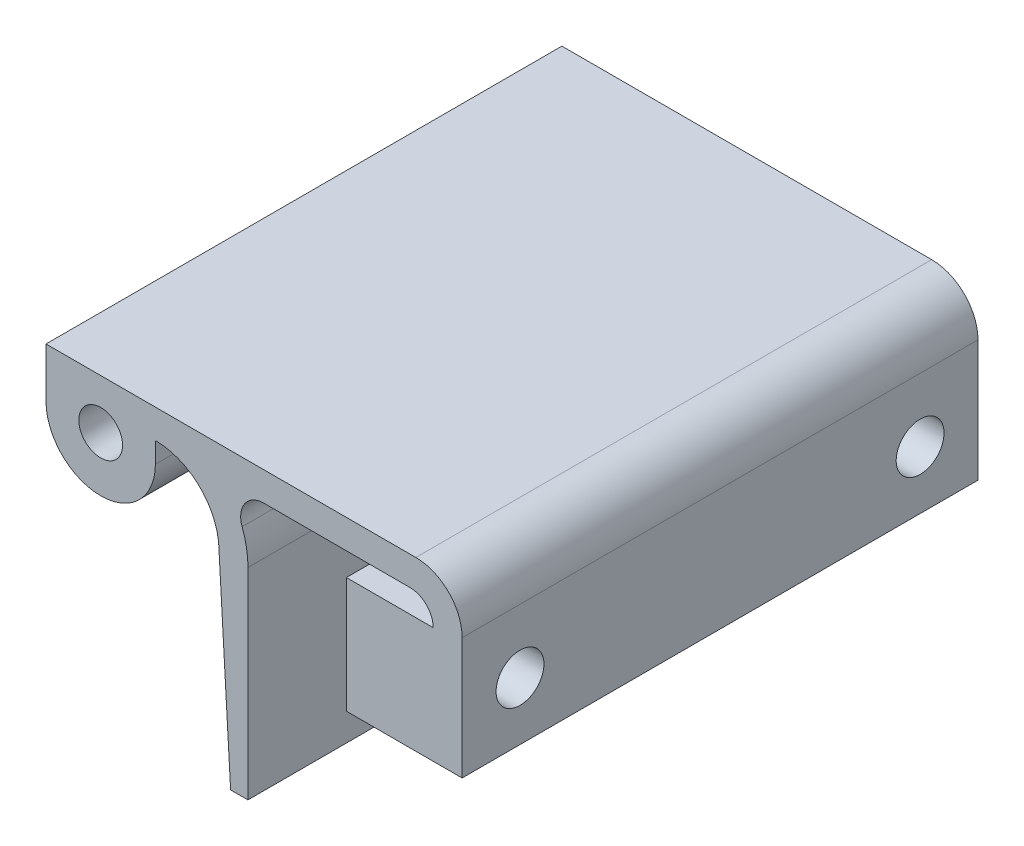
SolidWorks part; units mm, degrees
material "ABS"
ref_plane "X-Y Datum" through (0, 0, 0) normal (0, 0, 1) x (1, 0, 0)
ref_plane "X-Z Datum" through (0, 0, 0) normal (0, 1, 0) x (1, 0, 0)
ref_plane "Y-Z Datum" through (0, 0, 0) normal (1, 0, 0) x (0, 0, -1)
sketch "Sketch1" plane through (0, 0, 0) normal (0, 0, 1) x (1, 0, 0)
  line L0 (-77.4432, 182.1158) -> (-79.3482, 182.1026)
  line L1 (-76.1732, 214.3565) -> (-53.9482, 214.3565)
  line L2 (-53.9482, 214.3565) -> (-53.9482, 195.9415)
  line L3 (-79.3482, 182.1026) -> (-80.6182, 204.1965)
  line L4 (-77.4432, 182.1158) -> (-77.4432, 204.1965)
  line L12 (-87.6032, 214.3565) -> (-90.2382, 214.3565)
  line L14 (-99.6032, 214.3565) -> (-99.6032, 208.9265)
  line L15 (-87.6032, 211.1815) -> (-87.6032, 208.9265)
  line L16 (-99.6032, 214.3565) -> (-90.2382, 214.3565)
  line L17 (-87.6032, 214.3565) -> (-76.1732, 214.3565)
  line L19 (-59.6632, 211.1815) -> (-75.7065, 211.1815)
  line L20 (-57.1232, 208.6415) -> (-57.1232, 195.9415)
  line L21 (-57.1232, 195.9415) -> (-53.9482, 195.9415)
  arc A0 (-77.4432, 204.1965) -> (-87.6032, 214.3565) centre (-87.6032, 204.1965) ccw construction
  arc A1 (-80.6182, 204.1965) -> (-87.6032, 211.1815) centre (-87.6032, 204.1965) ccw
  arc A2 (-57.1232, 208.6415) -> (-59.6632, 211.1815) centre (-59.6632, 208.6415) ccw
  arc A3 (-77.4432, 204.1965) -> (-78.0858, 207.7525) centre (-87.6032, 204.1965) ccw
  arc A4 (-87.6032, 208.9265) -> (-99.6032, 208.9265) centre (-93.6032, 208.9265) cw
  circle A8 centre (-93.6032, 208.9265) radius 2.4
  arc A9 (-75.7065, 211.1815) -> (-78.0858, 207.7525) centre (-75.7065, 208.6415) ccw
  dimension "D1" = 2.54
  dimension "D2" = 3.175
extrude "Boss-Extrude1" add sketch "Sketch1" along normal blind 56.5988
sketch "Sketch7" plane through (-53.9482, 0, 0) normal (1, 0, 0) x (0, 0, -1)
  line L1 (-56.5988, 195.9415) -> (-43.8988, 195.9415)
  line L2 (-56.5988, 195.9415) -> (-56.5988, 208.6415)
  line L3 (-56.5988, 208.6415) -> (-43.8988, 208.6415)
  line L4 (-43.8988, 195.9415) -> (-43.8988, 208.6415)
  line L5 (0, 195.9415) -> (-12.7, 195.9415)
  line L6 (0, 195.9415) -> (0, 208.6415)
  line L7 (0, 208.6415) -> (-12.7, 208.6415)
  line L8 (-12.7, 195.9415) -> (-12.7, 208.6415)
extrude "Boss-Extrude3" add sketch "Sketch7" against normal blind 12.7
sketch "Sketch8" plane through (-53.9482, 0, 0) normal (1, 0, 0) x (0, 0, -1)
  circle A0 centre (-50.2488, 202.2915) radius 2.625
  circle A1 centre (-6.35, 202.2915) radius 2.625
extrude "Cut-Extrude2" cut sketch "Sketch8" against normal up to next
fillet "Fillet1" radius 5.08 1 edges at (-53.9482, 214.3565, 28.2994)
